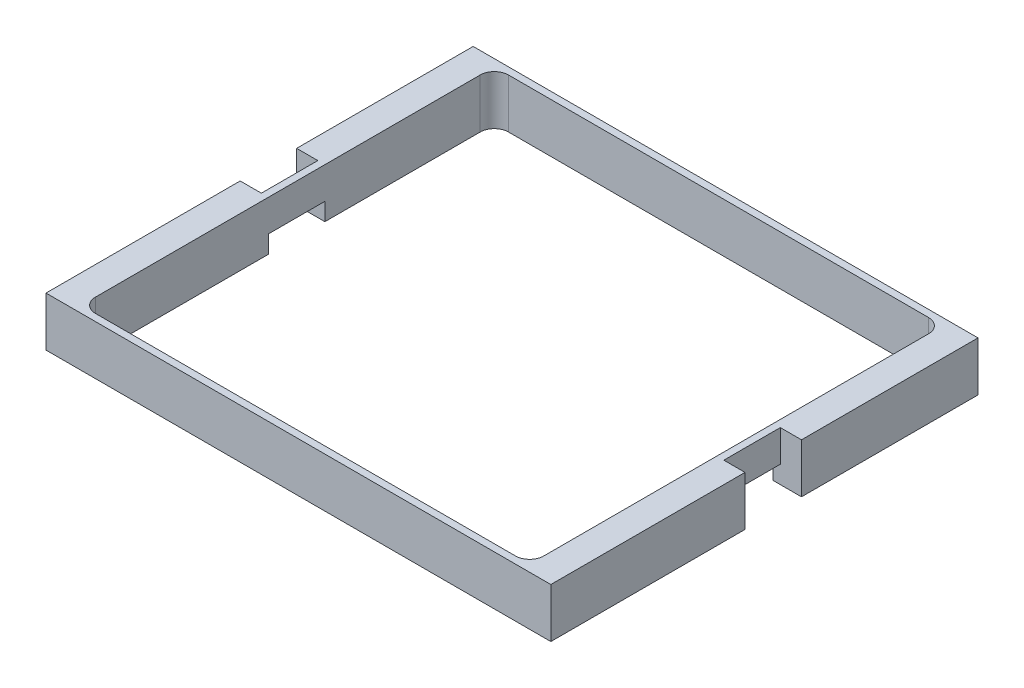
SolidWorks part; units mm, degrees
ref_plane "Спереди" through (0, 0, 0) normal (0, 0, 1) x (1, 0, 0)
ref_plane "Сверху" through (0, 0, 0) normal (0, 1, 0) x (1, 0, 0)
ref_plane "Справа" through (0, 0, 0) normal (1, 0, 0) x (0, 0, -1)
other "Configuration Table"
sketch "Эскиз1" plane through (0, 0, 0) normal (0, 1, 0) x (1, 0, 0)
  line L1 (0, 0) -> (63.5, 0)
  line L2 (0, 0) -> (0, -58.5)
  line L3 (0, -58.5) -> (63.5, -58.5)
  line L4 (63.5, 0) -> (63.5, -58.5)
  line L5 (-4, 1) -> (67.5, 1)
  line L6 (-4, 1) -> (-4, -59.5)
  line L7 (-4, -59.5) -> (67.5, -59.5)
  line L8 (67.5, 1) -> (67.5, -59.5)
  dimension "D1" = 63.5
  dimension "D2" = 58.5
  dimension "D3" = 1
  dimension "D4" = 1
  dimension "D5" = 4
  dimension "D6" = 4
extrude "Бобышка-Вытянуть1" add sketch "Эскиз1" along normal blind 7
fillet "Скругление1" radius 2 4 edges at (63.5, 3.5, 58.5) (0, 3.5, 58.5) (63.5, 3.5, 0) (0, 3.5, 0)
sketch "Эскиз2" plane through (0, 7, 0) normal (0, 1, 0) x (1, 0, 0)
  line L0 (-4, 1) -> (-4, -59.5) construction
  line L1 (-4, -24) -> (-1, -24)
  line L2 (-4, -24) -> (-4, -32)
  line L3 (-4, -32) -> (-1, -32)
  line L4 (-1, -24) -> (-1, -32)
  line L5 (61.5, 0) -> (2, 0) construction
  line L6 (67.5, -59.5) -> (67.5, 1) construction
  line L7 (67.5, -24) -> (64.5, -24)
  line L8 (67.5, -24) -> (67.5, -32)
  line L9 (67.5, -32) -> (64.5, -32)
  line L10 (64.5, -24) -> (64.5, -32)
  dimension "D1" = 8
  dimension "D2" = 24
  dimension "D3" = 3
  dimension "D4" = 3
extrude "Вырез-Вытянуть1" cut sketch "Эскиз2" against normal blind 7
sketch "Эскиз3" plane through (64.5, 0, 0) normal (1, 0, 0) x (0, 0, -1)
  line L0 (-24, 0) -> (-24, 7) construction
  line L1 (-32, 0) -> (-24, 0)
  line L2 (-32, 0) -> (-32, 2.5)
  line L3 (-32, 2.5) -> (-24, 2.5)
  line L4 (-24, 0) -> (-24, 2.5)
  dimension "D1" = 2.5
extrude "Вырез-Вытянуть2" cut sketch "Эскиз3" against normal through all
